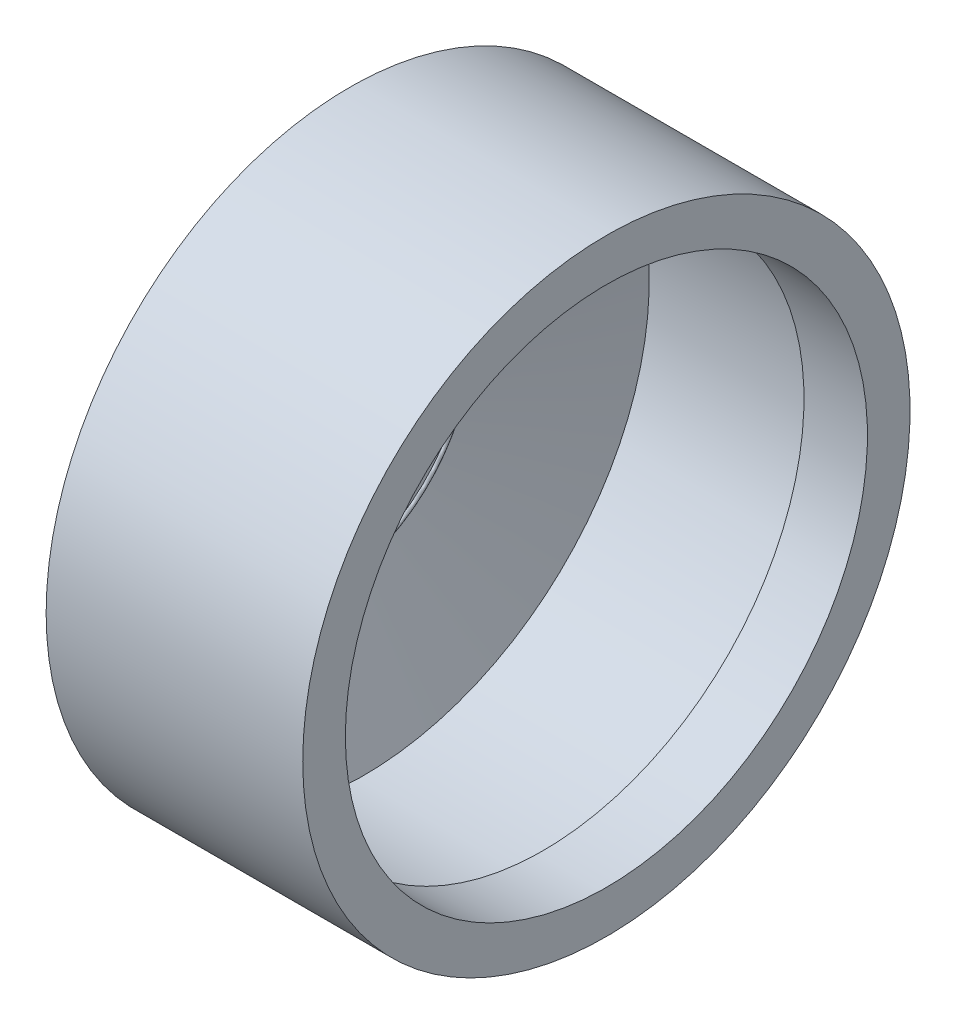
SolidWorks part; units mm, degrees
material "SBR"
ref_plane "Plano frontal" through (0, 0, 0) normal (0, 0, 1) x (1, 0, 0)
ref_plane "Plano superior" through (0, 0, 0) normal (0, 1, 0) x (1, 0, 0)
ref_plane "Plano direito" through (0, 0, 0) normal (1, 0, 0) x (0, 0, -1)
sketch "Esboço1" plane through (0, 0, 0) normal (0, 0, 1) x (1, 0, 0)
  line L0 (0, 0) -> (14, 0) construction
  line L1 (0.25, 3.5) -> (0.25, 8)
  line L2 (0.25, 8) -> (0, 8)
  line L3 (0, 8) -> (2.3446, 16.75)
  line L4 (2.3446, 16.75) -> (16.5, 16.75)
  line L5 (16.5, 16.75) -> (16.5, 14.4)
  line L6 (16.5, 14.4) -> (13, 14.4)
  line L7 (13, 14.4) -> (13, 15.75)
  line L8 (13, 15.75) -> (3.1119, 15.75)
  line L9 (3.1119, 15.75) -> (1, 7.8683)
  line L11 (1, 7.8683) -> (1, 3.5)
  line L12 (1, 3.5) -> (0.25, 3.5)
  line L13 (0, 8) -> (0, 12.9562) construction
  circle A0 centre (1, 7.8683) radius 0.125
  dimension "D12" = 0.25
  dimension "D1" = 7
  dimension "D2" = 16
  dimension "D3" = 3.5
  dimension "D4" = 33.5
  dimension "D5" = 28.8
  dimension "D6" = 16.5
  dimension "D7" = 1
  dimension "D8" = 1
  dimension "D9" = 0.25
  dimension "D10" = 15
  dimension "D11" = 0.75
revolve "Revolução1" add sketch "Esboço1" angle 360 about L0
